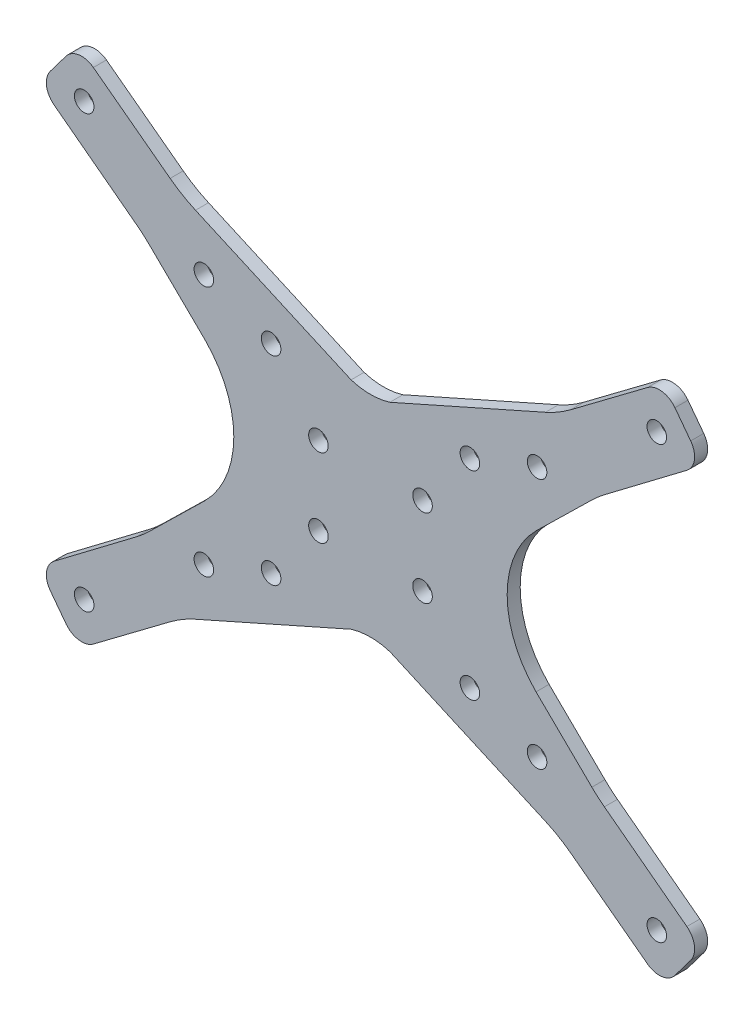
SolidWorks part; units mm, degrees
material "Thornel Mat VMA"
ref_plane "Alzado" through (0, 0, 0) normal (0, 0, 1) x (1, 0, 0)
ref_plane "Planta" through (0, 0, 0) normal (0, 1, 0) x (1, 0, 0)
ref_plane "Vista lateral" through (0, 0, 0) normal (1, 0, 0) x (0, 0, -1)
sketch "Croquis1" plane through (0, 0, 0) normal (0, 0, 1) x (1, 0, 0)
  line L0 (-802.3006, 384.0845) -> (-806.2938, 387.0936) construction
  line L1 (-806.2938, 387.0936) -> (-805.0872, 388.6948)
  line L2 (-800.8898, 389.2882) -> (-789.1106, 380.4421)
  line L3 (-785.2206, 378.1571) -> (-761.3509, 367.5524)
  line L4 (-806.2938, 387.0936) -> (-807.5011, 385.4914)
  line L5 (-806.9156, 381.2938) -> (-794.2596, 371.7159)
  line L6 (-792.341, 370.0629) -> (-783.7746, 361.6806)
  line L7 (-758.3757, 362.9807) -> (-758.3757, 355.9847) construction
  line L8 (-758.3757, 355.9847) -> (-763.3757, 350.9847) construction
  line L9 (-763.3757, 350.9847) -> (-770.8045, 350.9847) construction
  line L10 (-792.341, 331.9065) -> (-783.7746, 340.2888)
  line L11 (-806.9156, 320.6756) -> (-794.2596, 330.2534)
  line L12 (-806.2938, 314.8758) -> (-807.5011, 316.478)
  line L13 (-785.2206, 323.8123) -> (-761.3509, 334.417)
  line L14 (-800.8898, 312.6812) -> (-789.1106, 321.5273)
  line L15 (-806.2938, 314.8758) -> (-805.0872, 313.2746)
  line L16 (-710.4575, 314.8758) -> (-711.6641, 313.2746)
  line L17 (-715.8615, 312.6812) -> (-727.6407, 321.5273)
  line L18 (-731.5307, 323.8123) -> (-755.4004, 334.417)
  line L19 (-710.4575, 314.8758) -> (-709.2502, 316.478)
  line L20 (-709.8357, 320.6756) -> (-722.4917, 330.2534)
  line L21 (-724.4103, 331.9065) -> (-732.9767, 340.2888)
  line L22 (-724.4103, 370.0629) -> (-732.9767, 361.6806)
  line L23 (-709.8357, 381.2938) -> (-722.4917, 371.7159)
  line L24 (-710.4575, 387.0936) -> (-709.2502, 385.4914)
  line L25 (-731.5307, 378.1571) -> (-755.4004, 367.5524)
  line L26 (-715.8615, 389.2882) -> (-727.6407, 380.4421)
  line L27 (-710.4575, 387.0936) -> (-711.6641, 388.6948)
  arc A0 (-807.5011, 385.4914) -> (-806.9156, 381.2938) centre (-805.1052, 383.686) ccw
  arc A1 (-805.0872, 388.6948) -> (-800.8898, 389.2882) centre (-802.6913, 386.8893) cw
  arc A2 (-805.0872, 313.2746) -> (-800.8898, 312.6812) centre (-802.6913, 315.08) ccw
  arc A3 (-807.5011, 316.478) -> (-806.9156, 320.6756) centre (-805.1052, 318.2834) cw
  arc A4 (-709.2502, 316.478) -> (-709.8357, 320.6756) centre (-711.6461, 318.2834) ccw
  arc A5 (-711.6641, 313.2746) -> (-715.8615, 312.6812) centre (-714.06, 315.08) cw
  arc A6 (-711.6641, 388.6948) -> (-715.8615, 389.2882) centre (-714.06, 386.8893) ccw
  arc A7 (-709.2502, 385.4914) -> (-709.8357, 381.2938) centre (-711.6461, 383.686) cw
  arc A8 (-783.7746, 361.6806) -> (-783.7746, 340.2888) centre (-794.4706, 350.9847) cw
  arc A9 (-732.9767, 340.2888) -> (-732.9767, 361.6806) centre (-722.2807, 350.9847) cw
  arc A10 (-761.3509, 367.5524) -> (-755.4004, 367.5524) centre (-758.3757, 377.0996) ccw
  arc A11 (-761.3509, 334.417) -> (-755.4004, 334.417) centre (-758.3757, 324.8698) cw
  arc A12 (-789.1106, 380.4421) -> (-785.2206, 378.1571) centre (-777.1005, 396.4345) ccw
  arc A13 (-794.2596, 371.7159) -> (-792.341, 370.0629) centre (-806.3287, 355.768) cw
  arc A14 (-792.341, 331.9065) -> (-794.2596, 330.2534) centre (-806.3287, 346.2014) cw
  arc A15 (-785.2206, 323.8123) -> (-789.1106, 321.5273) centre (-777.1005, 305.5349) ccw
  arc A16 (-727.6407, 321.5273) -> (-731.5307, 323.8123) centre (-739.6508, 305.5349) ccw
  arc A17 (-722.4917, 330.2534) -> (-724.4103, 331.9065) centre (-710.4226, 346.2014) cw
  arc A18 (-724.4103, 370.0629) -> (-722.4917, 371.7159) centre (-710.4226, 355.768) cw
  arc A19 (-731.5307, 378.1571) -> (-727.6407, 380.4421) centre (-739.6508, 396.4345) ccw
  circle A20 centre (-802.3006, 384.0845) radius 1.5
  circle A21 centre (-783.9359, 370.2457) radius 1.5
  circle A22 centre (-766.362, 357.0028) radius 1.5
  circle A23 centre (-773.6257, 366.2347) radius 1.5
  circle A24 centre (-750.3893, 357.0028) radius 1.5
  circle A25 centre (-743.1257, 366.2347) radius 1.5
  circle A26 centre (-732.8154, 370.2457) radius 1.5
  circle A27 centre (-714.4507, 384.0845) radius 1.5
  circle A28 centre (-714.4507, 317.8849) radius 1.5
  circle A29 centre (-732.8154, 331.7236) radius 1.5
  circle A30 centre (-743.1257, 335.7347) radius 1.5
  circle A31 centre (-750.3893, 344.9665) radius 1.5
  circle A32 centre (-766.362, 344.9665) radius 1.5
  circle A33 centre (-773.6257, 335.7347) radius 1.5
  circle A34 centre (-783.9359, 331.7236) radius 1.5
  circle A35 centre (-802.3006, 317.8849) radius 1.5
  point P27 (-803.2847, 310.8826)
  point P28 (-809.3029, 318.869)
  point P41 (-707.4484, 318.869)
  point P42 (-713.4666, 310.8826)
  dimension "D1" = 5
  dimension "D2" = 3
  dimension "D3" = 20
extrude "Saliente-Extruir1" add sketch "Croquis1" along normal blind 2
